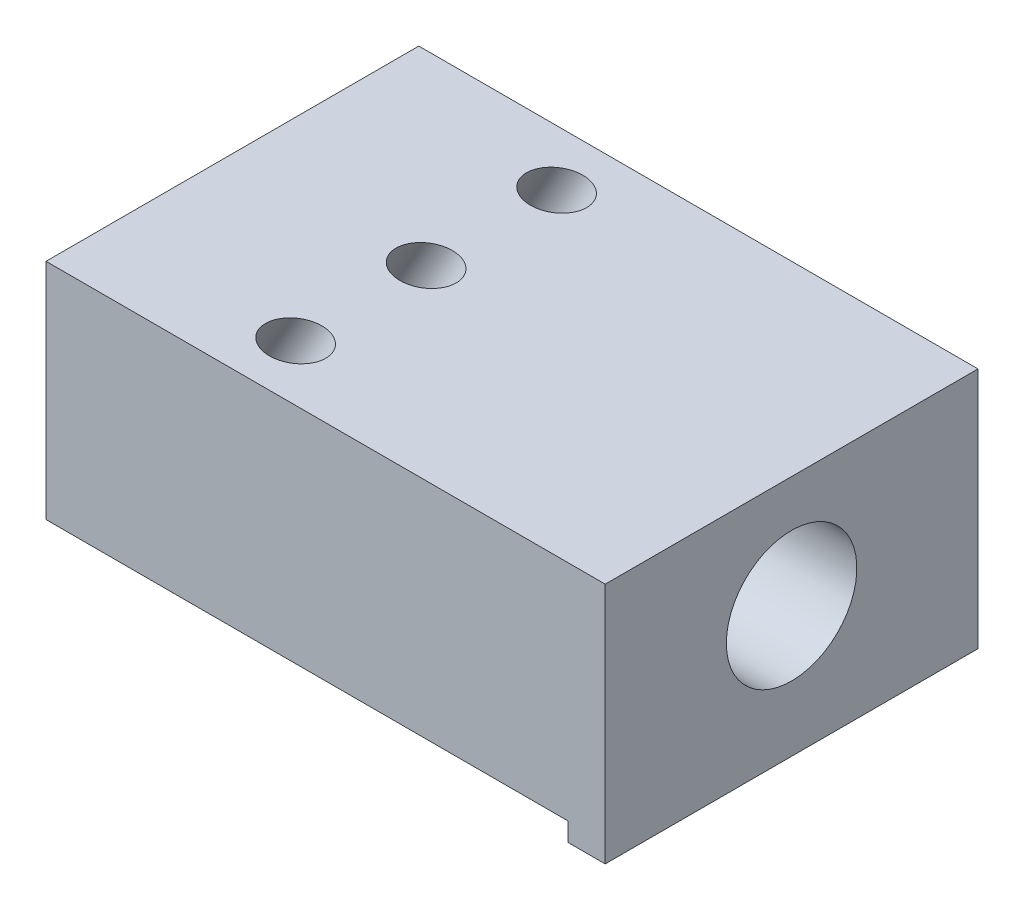
SolidWorks part; units mm, degrees
ref_plane "Front Plane" through (0, 0, 0) normal (0, 0, 1) x (1, 0, 0)
ref_plane "Top Plane" through (0, 0, 0) normal (0, 1, 0) x (1, 0, 0)
ref_plane "Right Plane" through (0, 0, 0) normal (1, 0, 0) x (0, 0, -1)
sketch "Skica1" plane through (0, 0, 0) normal (0, 0, 1) x (1, 0, 0)
  line L1 (0, 0) -> (30, 0)
  line L2 (0, 0) -> (0, 12)
  line L3 (0, 12) -> (30, 12)
  line L4 (30, 0) -> (30, 12)
  line L5 (30, 0) -> (28, 0)
  line L6 (30, 0) -> (30, -1)
  line L7 (30, -1) -> (28, -1)
  line L8 (28, 0) -> (28, -1)
  dimension "D1" = 12
  dimension "D2" = 1
  dimension "D3" = 2
  dimension "D4" = 30
extrude "Přidat vysunutím1" add sketch "Skica1" along normal blind 20 contours L1 L4 L3 L2 | L1 L8 L7 L6
sketch "Skica2" plane through (0, 0, 0) normal (-1, 0, 0) x (0, 0, 1)
  line L0 (0, 12) -> (20, 0) construction
  circle A0 centre (10, 6) radius 3.5
  dimension "D1" = 7
extrude "Odebrat vysunutím1" cut sketch "Skica2" against normal blind 34
ref_plane "Rovina1" through (0, 0, 0) normal (-0.5, -0.866, 0) x (0, 0, -1)
sketch "Skica3" plane through (0, 0, 0) normal (-0.5, -0.866, 0) x (0, 0, -1)
  line L0 (-20, 3) -> (0, 3) construction
  line L1 (-20, 0) -> (-20, 24.2487) construction
  line L2 (0, 0) -> (0, 24.2487) construction
  line L3 (-10, 3) -> (-10, 8.0134) construction
  line L4 (-20, 0) -> (0, 0) construction
  circle A0 centre (-10, 3) radius 1.4
  circle A1 centre (-17, 3) radius 1.4
  circle A2 centre (-3, 3) radius 1.4
  dimension "D1" = 2.8
  dimension "D2" = 2.8
  dimension "D3" = 3
  dimension "D4" = 3
extrude "Odebrat vysunutím2" cut sketch "Skica3" against normal blind 34
